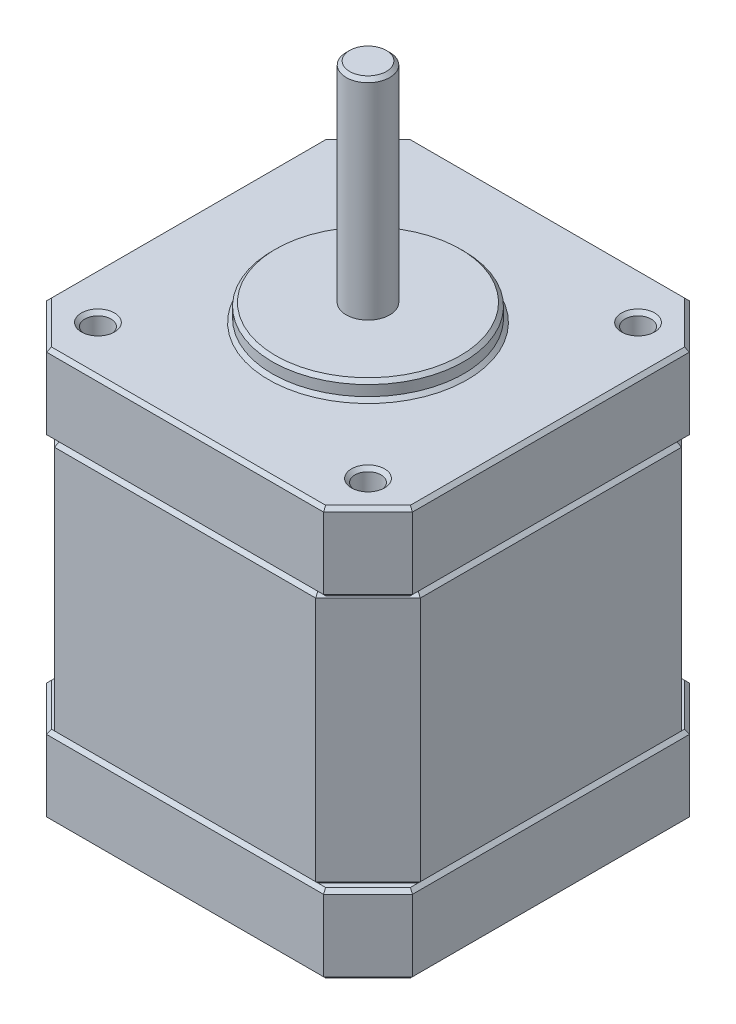
SolidWorks part; units mm, degrees
ref_plane "Front Plane" through (0, 0, 0) normal (0, 0, 1) x (1, 0, 0)
ref_plane "Top Plane" through (0, 0, 0) normal (0, 1, 0) x (1, 0, 0)
ref_plane "Right Plane" through (0, 0, 0) normal (1, 0, 0) x (0, 0, -1)
sketch "Sketch1" plane through (0, 0, 0) normal (0, 1, 0) x (1, 0, 0)
  line L1 (-21, -21) -> (21, -21)
  line L2 (-21, -21) -> (-21, 21)
  line L3 (-21, 21) -> (21, 21)
  line L4 (21, -21) -> (21, 21)
  line L5 (-21, -21) -> (21, 21) construction
  line L6 (-21, 21) -> (21, -21) construction
  point P0 (0, 0)
  dimension "D1" = 42
extrude "Boss-Extrude1" add sketch "Sketch1" along normal blind 9
chamfer "Chamfer1" distance 5.1 angle 45 4 edges at (-21, 4.5, -21) (21, 4.5, -21) (21, 4.5, 21) (-21, 4.5, 21)
chamfer "Chamfer2" distance 0.4 angle 45 16 edges at (-18.45, 0, 18.45) (0, 0, 21) (18.45, 0, 18.45) (21, 0, 0) (18.45, 0, -18.45) (0, 0, -21) (-18.45, 0, -18.45) (-21, 0, 0) (18.45, 9, -18.45) (21, 9, 0) (18.45, 9, 18.45) (0, 9, 21) (-18.45, 9, 18.45) (-21, 9, 0) (-18.45, 9, -18.45) (0, 9, -21)
sketch "Sketch3" plane through (0, 9, 0) normal (0, 1, 0) x (1, 0, 0)
  line L1 (21, 21) -> (-21, 21)
  line L2 (21, 21) -> (21, -21)
  line L3 (21, -21) -> (-21, -21)
  line L4 (-21, 21) -> (-21, -21)
  line L5 (21, 21) -> (-21, -21) construction
  line L6 (21, -21) -> (-21, 21) construction
  point P0 (0, 0)
  dimension "D1" = 42
extrude "Boss-Extrude3" add sketch "Sketch3" along normal blind 29 separate body
chamfer "Chamfer3" distance 6 angle 45 4 edges at (-21, 23.5, -21) (21, 23.5, -21) (-21, 23.5, 21) (21, 23.5, 21)
chamfer "Chamfer4" distance 0.4 angle 45 16 edges at (18, 38, -18) (21, 38, 0) (18, 38, 18) (0, 38, 21) (-18, 38, 18) (-21, 38, 0) (-18, 38, -18) (0, 38, -21) (-18, 9, 18) (0, 9, 21) (18, 9, 18) (21, 9, 0) (18, 9, -18) (0, 9, -21) (-18, 9, -18) (-21, 9, 0)
sketch "Sketch4" plane through (0, 38, 0) normal (0, 1, 0) x (1, 0, 0)
  line L1 (21, 21) -> (-21, 21)
  line L2 (21, 21) -> (21, -21)
  line L3 (21, -21) -> (-21, -21)
  line L4 (-21, 21) -> (-21, -21)
  line L5 (21, 21) -> (-21, -21) construction
  line L6 (21, -21) -> (-21, 21) construction
  point P0 (0, 0)
  dimension "D1" = 42
extrude "Boss-Extrude4" add sketch "Sketch4" along normal blind 9 separate body
chamfer "Chamfer5" distance 5.1 angle 45 4 edges at (21, 42.5, 21) (-21, 42.5, 21) (-21, 42.5, -21) (21, 42.5, -21)
sketch "Sketch5" plane through (0, 47, 0) normal (0, 1, 0) x (1, 0, 0)
  circle A0 centre (0, 0) radius 11
  dimension "D1" = 22
extrude "Boss-Extrude5" add sketch "Sketch5" along normal blind 2
sketch "Sketch7" plane through (0, 47, 0) normal (0, 1, 0) x (1, 0, 0)
  line L1 (15.5, 15.5) -> (-15.5, 15.5) construction
  line L2 (15.5, 15.5) -> (15.5, -15.5) construction
  line L3 (15.5, -15.5) -> (-15.5, -15.5) construction
  line L4 (-15.5, 15.5) -> (-15.5, -15.5) construction
  line L5 (15.5, 15.5) -> (-15.5, -15.5) construction
  line L6 (15.5, -15.5) -> (-15.5, 15.5) construction
  circle A0 centre (15.5, -15.5) radius 1.5
  circle A1 centre (-15.5, -15.5) radius 1.5
  circle A2 centre (15.5, 15.5) radius 1.5
  circle A3 centre (-15.5, 15.5) radius 1.5
  point P0 (0, 0)
  point P11 (-15.5, 14.9023)
  dimension "D2" = 3
  dimension "D1" = 31
extrude "Cut-Extrude1" cut sketch "Sketch7" against normal blind 5
chamfer "Chamfer6" distance 0.4 angle 45 26 edges at (-18.45, 47, 18.45) (-21, 47, 0) (-18.45, 47, -18.45) (0, 47, -21) (18.45, 47, -18.45) (21, 47, 0) (18.45, 47, 18.45) (0, 47, 21) (18.45, 38, -18.45) (0, 38, -21) (-18.45, 38, -18.45) (-21, 38, 0) (-18.45, 38, 18.45) (0, 38, 21) (18.45, 38, 18.45) (21, 38, 0) (0, 47, 11) (0, 49, 11) (15.5, 47, 17) (-15.5, 47, -14) (15.5, 47, -14) (-15.5, 47, 17) (-15.5, 42, 17) (-15.5, 42, -14) (15.5, 42, -14) (15.5, 42, 17)
sketch "Sketch6" plane through (0, 49, 0) normal (0, 1, 0) x (1, 0, 0)
  circle A0 centre (0, 0) radius 2.5
  dimension "D1" = 5
extrude "Boss-Extrude6" add sketch "Sketch6" along normal blind 24 separate body
chamfer "Chamfer7" distance 0.4 angle 45 1 edges at (0, 73, 2.5)
